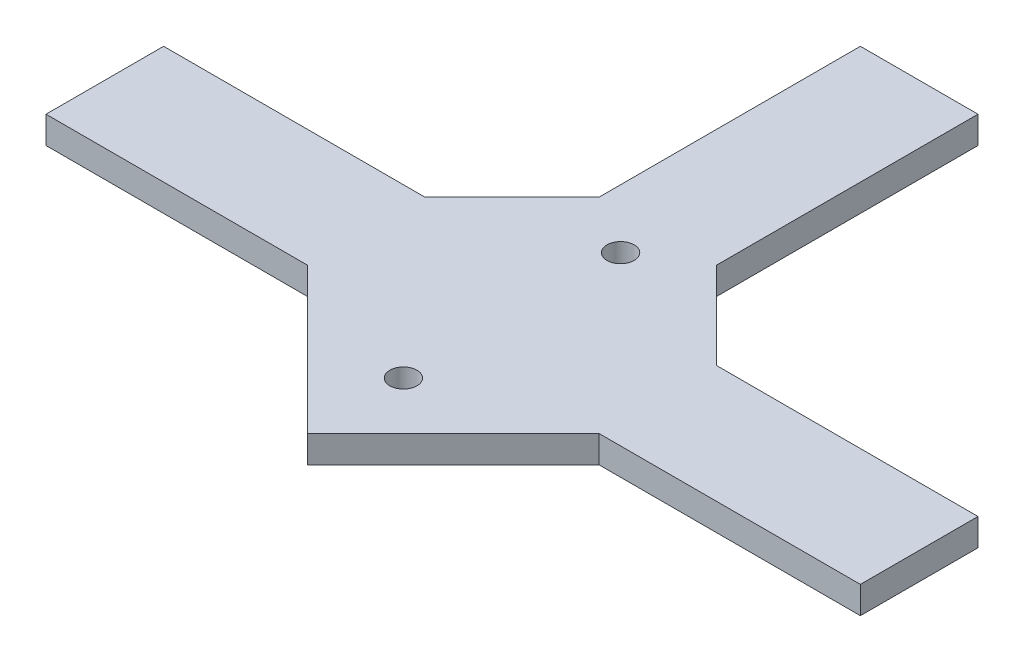
SolidWorks part; units mm, degrees
ref_plane "Plano frontal" through (0, 0, 0) normal (0, 0, 1) x (1, 0, 0)
ref_plane "Plano superior" through (0, 0, 0) normal (0, 1, 0) x (1, 0, 0)
ref_plane "Plano direito" through (0, 0, 0) normal (1, 0, 0) x (0, 0, -1)
sketch "Esboço1" plane through (0, 0, 0) normal (0, 1, 0) x (1, 0, 0)
  line L0 (0, 22.6274) -> (-22.6274, 0)
  line L1 (0, 22.6274) -> (22.6274, 0)
  line L2 (-22.6274, 0) -> (0, -22.6274)
  line L3 (22.6274, 0) -> (0, -22.6274)
  line L4 (0, 22.6274) -> (0, -22.6274) construction
  line L5 (-22.6274, 0) -> (22.6274, 0) construction
  line L6 (-16.1274, 6.5) -> (-45, 6.5)
  line L7 (-45, 6.5) -> (-45, -6.5)
  line L8 (-16.1274, -6.5) -> (-45, -6.5)
  line L9 (16.1274, -6.5) -> (45, -6.5)
  line L10 (45, 6.5) -> (45, -6.5)
  line L11 (16.1274, 6.5) -> (45, 6.5)
  line L12 (6.5, 16.1274) -> (6.5, 45)
  line L13 (6.5, 45) -> (-6.5, 45)
  line L14 (-6.5, 16.1274) -> (-6.5, 45)
  circle A0 centre (0, 12) radius 1.5
  circle A2 centre (0, -12) radius 1.5
  circle A4 centre (12, 0) radius 1.5 [skipped]
  circle A5 centre (-12, 0) radius 1.5 [skipped]
  point P1 (0, 0)
  point P10 (-45, 0)
  point P11 (45, 0)
  point P18 (0, 0)
  point P21 (0, 0)
  point P24 (0, 0)
  point P27 (0, 0)
  point P29 (0, 0)
  point P30 (0, 45)
  point P31 (0, 0)
  point P32 (0, 0)
  dimension "D5" = 3
  dimension "D4" = 24
  dimension "D1" = 32
  dimension "D2" = 13
  dimension "D3" = 45
  dimension "D6" = 4
  dimension "D7" = 2
extrude "Ressalto-extrusão1" add sketch "Esboço1" along normal blind 3
